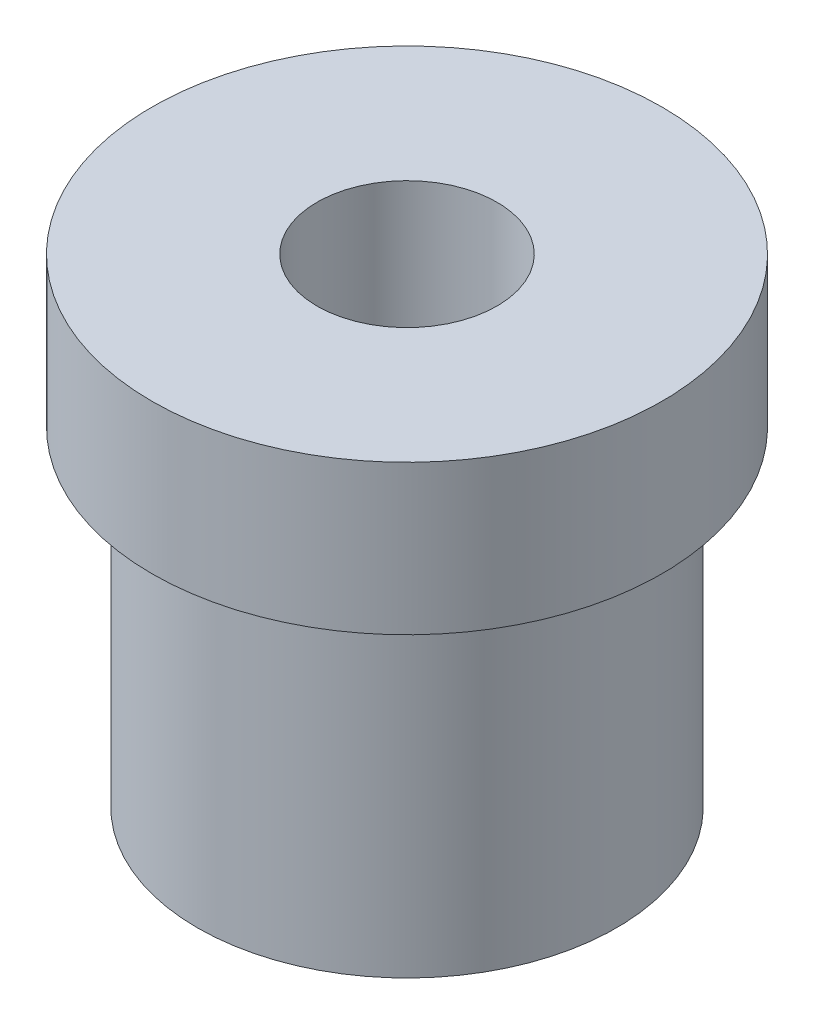
SolidWorks part; units mm, degrees
ref_plane "Plane1" through (0, 0, 0) normal (0, 0, 1) x (1, 0, 0)
ref_plane "Plane2" through (0, 0, 0) normal (0, 1, 0) x (1, 0, 0)
ref_plane "Plane3" through (0, 0, 0) normal (1, 0, 0) x (0, 0, -1)
sketch "Sketch1" plane through (0, 0, 0) normal (0, 1, 0) x (1, 0, 0)
  circle A0 centre (0, 0) radius 5.5562
  dimension "D1" = 11.1125
extrude "Base-Extrude" add sketch "Sketch1" against normal blind 12.7
sketch "Sketch2" plane through (0, 0, 0) normal (0, 1, 0) x (-1, 0, 0)
  circle A0 centre (0, 0) radius 6.7627
  dimension "D1" = 13.5255
extrude "Boss-Extrude1" add sketch "Sketch2" against normal blind 3.9624
sketch "Sketch3" plane through (0, 0, 0) normal (0, 1, 0) x (-1, 0, 0)
  circle A0 centre (0, 0) radius 2.3876
  dimension "D1" = 4.7752
extrude "Cut-Extrude1" cut sketch "Sketch3" against normal through all
